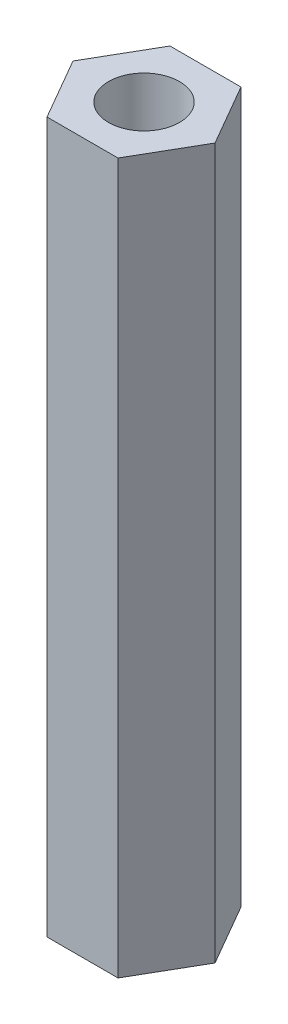
SolidWorks part; units mm, degrees
ref_plane "Front Plane" through (0, 0, 0) normal (0, 0, 1) x (1, 0, 0)
ref_plane "Top Plane" through (0, 0, 0) normal (0, 1, 0) x (1, 0, 0)
ref_plane "Right Plane" through (0, 0, 0) normal (1, 0, 0) x (0, 0, -1)
sketch "Sketch1" plane through (0, 0, 0) normal (0, 1, 0) x (1, 0, 0)
  line L1 (-0.25, 0.433) -> (-0.5, 0)
  line L2 (-0.5, 0) -> (-0.25, -0.433)
  line L3 (-0.25, -0.433) -> (0.25, -0.433)
  line L4 (0.25, -0.433) -> (0.5, 0)
  line L5 (0.5, 0) -> (0.25, 0.433)
  line L6 (0.25, 0.433) -> (-0.25, 0.433)
  circle A0 centre (0, 0) radius 0.433 construction
  circle A1 centre (0, 0) radius 0.25
  dimension "D2" = 0.5
  dimension "D1" = 1
extrude "Boss-Extrude2" add sketch "Sketch1" along normal blind 5
